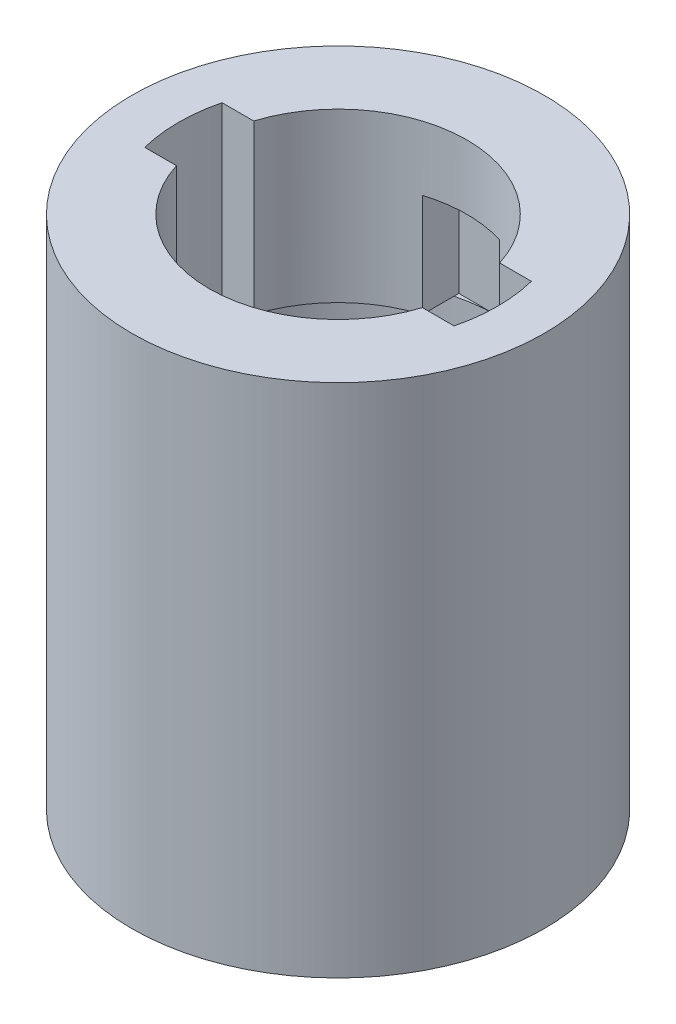
SolidWorks part; units mm, degrees
ref_plane "Спереди" through (0, 0, 0) normal (0, 0, 1) x (1, 0, 0)
ref_plane "Сверху" through (0, 0, 0) normal (0, 1, 0) x (1, 0, 0)
ref_plane "Справа" through (0, 0, 0) normal (1, 0, 0) x (0, 0, -1)
sketch "Эскиз1" plane through (0, 0, 0) normal (0, 1, 0) x (1, 0, 0)
  circle A0 centre (0, 0) radius 5
  circle A1 centre (0, 0) radius 8
  dimension "D1" = 10
  dimension "D2" = 16
extrude "Вытянуть1" add sketch "Эскиз1" along normal blind 20
sketch "Эскиз2" plane through (0, 20, 0) normal (0, 1, 0) x (1, 0, 0)
  line L1 (-6, 1.5) -> (6, 1.5)
  line L3 (-6, -1.5) -> (6, -1.5)
  arc A0 (-6, 1.5) -> (-6, -1.5) centre (0, 0) ccw
  arc A1 (6, 1.5) -> (6, -1.5) centre (0, 0) cw
  point P4 (6.1847, 0)
  point P5 (0, 1.5)
  dimension "D1" = 12
  dimension "D2" = 3
extrude "Вытянуть2" cut sketch "Эскиз2" against normal blind 9.5
sketch "Эскиз4" plane through (0, 0, 0) normal (0, 0, 1) x (1, 0, 0)
  line L1 (0, 10.5) -> (6, 10.5)
  line L2 (0, 10.5) -> (0, 13.5)
  line L3 (0, 13.5) -> (6, 13.5)
  line L4 (6.1847, 13.5) -> (6.1847, 10.5)
  line L5 (0, 0) -> (0, 20) construction
  line L6 (8, 20) -> (-8, 20) construction
  line L7 (6, 13.5) -> (6.1847, 13.5)
  line L8 (6, 10.5) -> (6.1847, 10.5)
  arc A0 (6, 13.5) -> (6, 10.5) centre (0, 12) cw construction
  point P6 (0, 12)
  dimension "D1" = 3
  dimension "D2" = 6
  dimension "D3" = 8
revolve "Вырез-Повернуть2" cut sketch "Эскиз4" angle 360 about L5
sketch "Эскиз5" plane through (0, 13.5, 0) normal (0, -1, 0) x (1, 0, 0)
  line L0 (-1.5, 6.1847) -> (1.5, 6.1847)
  line L1 (-1.5, -6) -> (1.5, -6) construction
  line L2 (-1.5, -6) -> (-1.5, 6)
  line L3 (-1.5, 6) -> (1.5, 6) construction
  line L4 (1.5, -6) -> (1.5, 6)
  line L5 (1.5, -6.1847) -> (-1.5, -6.1847)
  line L6 (1.5, 6) -> (1.5, 6.1847)
  line L7 (-1.5, 6) -> (-1.5, 6.1847)
  line L8 (-1.5, -6) -> (-1.5, -6.1847)
  line L9 (1.5, -6.1847) -> (1.5, -6)
  arc A1 (-1.5, 6) -> (1.5, 6) centre (0, 0) cw construction
  arc A2 (-1.5, -6) -> (1.5, -6) centre (0, 0) ccw construction
  point P4 (1.5, 0)
  point P6 (0, -6)
  dimension "D1" = 12
  dimension "D2" = 3
extrude "Вытянуть3" cut sketch "Эскиз5" against normal blind 4
